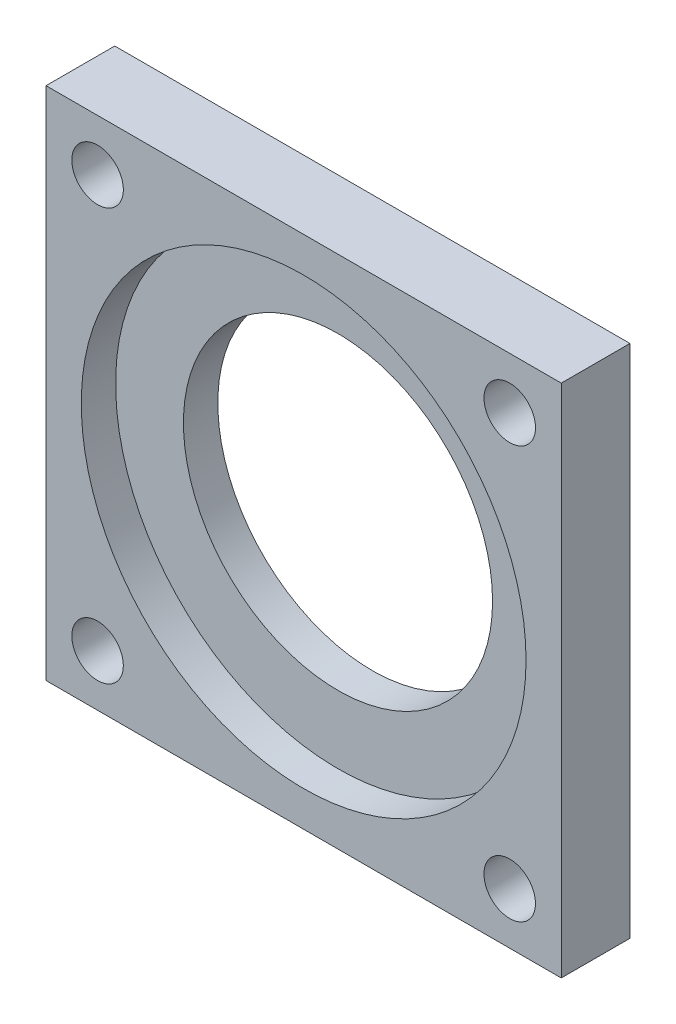
SolidWorks part; units mm, degrees
ref_plane "Plano frontal" through (0, 0, 0) normal (0, 0, 1) x (1, 0, 0)
ref_plane "Plano superior" through (0, 0, 0) normal (0, 1, 0) x (1, 0, 0)
ref_plane "Plano direito" through (0, 0, 0) normal (1, 0, 0) x (0, 0, -1)
sketch "Esboço1" plane through (0, 0, 0) normal (0, 0, 1) x (1, 0, 0)
  line L0 (15, 15) -> (-15, -15) construction
  line L1 (-15, 15) -> (15, 15)
  line L2 (-15, 15) -> (-15, -15)
  line L3 (-15, -15) -> (15, -15)
  line L4 (15, 15) -> (15, -15)
  line L5 (-15, -15) -> (-15, -15.4507) construction
  line L6 (0, -15) -> (0, 0) construction
  line L7 (0, 0) -> (15, 0) construction
  circle A0 centre (-12, -12) radius 1.5
  circle A1 centre (12, -12) radius 1.5
  circle A2 centre (12, 12) radius 1.5
  circle A3 centre (-12, 12) radius 1.5
  dimension "D5" = 3
  dimension "D1" = 30
  dimension "D2" = 30
  dimension "D3" = 3
  dimension "D4" = 3
extrude "Ressalto-extrusão1" add sketch "Esboço1" along normal blind 4
sketch "Esboço2" plane through (0, 0, 4) normal (0, 0, 1) x (1, 0, 0)
  circle A0 centre (0, 0) radius 9
  dimension "D1" = 18
extrude "Corte-extrusão1" cut sketch "Esboço2" against normal up to next
sketch "Esboço4" plane through (0, 0, 4) normal (0, 0, 1) x (1, 0, 0)
  circle A0 centre (0, 0) radius 12.95
  dimension "D1" = 25.9
extrude "Corte-extrusão2" cut sketch "Esboço4" against normal blind 2
